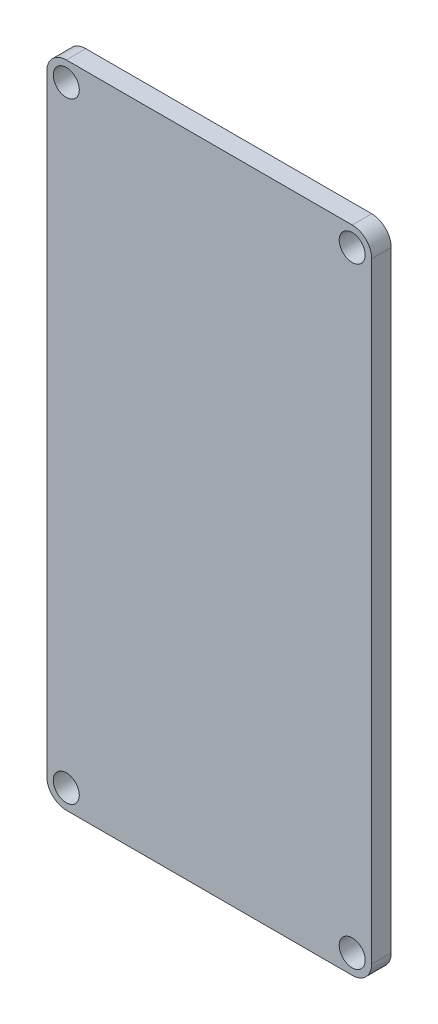
SolidWorks part; units mm, degrees
ref_plane "Front Plane" through (0, 0, 0) normal (0, 0, 1) x (1, 0, 0)
ref_plane "Top Plane" through (0, 0, 0) normal (0, 1, 0) x (1, 0, 0)
ref_plane "Right Plane" through (0, 0, 0) normal (1, 0, 0) x (0, 0, -1)
sketch "Sketch1" plane through (0, 0, 0) normal (0, 0, 1) x (1, 0, 0)
  line L1 (-22.007, -50.0002) -> (21.993, -50.0002)
  line L2 (-25.007, -47.0002) -> (-25.007, 46.9998)
  line L3 (-22.007, 49.9998) -> (21.993, 49.9998)
  line L4 (24.993, -47.0002) -> (24.993, 46.9998)
  line L5 (-25.007, -50.0002) -> (24.993, 49.9998) construction
  line L6 (-25.007, 49.9998) -> (24.993, -50.0002) construction
  line L7 (-22.007, -47.0002) -> (21.993, -47.0002)
  line L8 (-22.007, -47.0002) -> (-22.007, 46.9998)
  line L9 (-22.007, 46.9998) -> (21.993, 46.9998)
  line L10 (21.993, -47.0002) -> (21.993, 46.9998)
  line L11 (-22.007, -47.0002) -> (21.993, 46.9998) construction
  line L12 (-22.007, 46.9998) -> (21.993, -47.0002) construction
  arc A0 (-22.007, -50.0002) -> (-25.007, -47.0002) centre (-22.007, -47.0002) cw
  arc A1 (21.993, -50.0002) -> (24.993, -47.0002) centre (21.993, -47.0002) ccw
  arc A2 (21.993, 49.9998) -> (24.993, 46.9998) centre (21.993, 46.9998) cw
  arc A3 (-25.007, 46.9998) -> (-22.007, 49.9998) centre (-22.007, 46.9998) cw
  circle A4 centre (-22.007, 46.9998) radius 2
  circle A5 centre (21.993, 46.9998) radius 2
  circle A6 centre (21.993, -47.0002) radius 2
  circle A7 centre (-22.007, -47.0002) radius 2
  circle A8 centre (-22.007, 46.9998) radius 3
  circle A9 centre (21.993, 46.9998) radius 3
  circle A10 centre (21.993, -47.0002) radius 3
  circle A11 centre (-22.007, -47.0002) radius 3
  point P0 (-0.007, -0.0002)
  point P26 (-0.007, -0.0002)
  dimension "D3" = 3
  dimension "D4" = 4
  dimension "D1" = 100
  dimension "D2" = 50
extrude "Boss-Extrude1" add sketch "Sketch1" along normal blind 3 contours A9 L3 A8 L9 | L9 A8 A3 L8 A4 | A11 L7 A10 L10 A9 L9 A8 L8 | L8 A8 L9 A4 | A11 L8 A8 L2 | A2 A9 L9 A5 L10 | A10 L4 A9 L10 | L9 A9 L10 A5 | A1 A10 L10 A6 L7 | L10 A10 L7 A6 | A11 L1 A10 L7 | L8 A11 A0 L7 A7 | L7 A11 L8 A7
sketch "Sketch2" plane through (0, 0, 0) normal (0, 0, -1) x (-1, 0, 0)
  line L0 (12.5987, -31.1646) -> (12.5987, -29.7948)
  line L2 (12.5987, -29.7948) -> (20.007, -29.7948)
  line L3 (20.007, -29.7948) -> (20.007, -30.4596)
  line L4 (20.007, -30.4596) -> (13.3585, -30.4596)
  line L5 (13.3585, -30.4596) -> (13.3585, -31.5994)
  line L6 (13.3585, -31.5994) -> (12.5987, -31.1646)
  line L7 (14.8782, -11.6729) -> (14.8782, -12.3377)
  line L8 (17.2705, -9.1812) -> (19.2472, -11.0347)
  line L9 (19.2472, -11.0347) -> (19.2472, -7.5888)
  line L10 (19.2472, -7.5888) -> (20.007, -7.5888)
  line L11 (20.007, -7.5888) -> (20.007, -12.6227)
  line L12 (20.007, -12.6227) -> (16.941, -9.7496)
  line L13 (14.3083, 8.4436) -> (14.3083, 7.7787)
  line L14 (18.0125, 7.4938) -> (18.0125, 8.1587)
  line L15 (16.3029, 9.5833) -> (15.543, 9.5833)
  line L16 (12.4087, 31.6543) -> (12.4087, 31.7893)
  line L17 (12.4087, 31.7893) -> (17.5376, 31.7893)
  line L18 (17.5376, 31.7893) -> (17.5376, 32.6442)
  line L19 (17.5376, 32.6442) -> (18.2974, 32.6442)
  line L20 (18.2974, 32.6442) -> (18.2974, 31.7893)
  line L21 (18.2974, 31.7893) -> (20.007, 31.7893)
  line L22 (20.007, 31.7893) -> (20.007, 31.1245)
  line L23 (20.007, 31.1245) -> (18.2974, 31.1245)
  line L24 (18.2974, 31.1245) -> (18.2974, 27.6103)
  line L25 (18.2974, 27.6103) -> (12.4087, 31.6543)
  line L26 (17.5376, 31.1245) -> (14.3232, 31.1245)
  line L27 (14.3232, 31.1245) -> (17.5376, 28.9177)
  line L28 (17.5376, 28.9177) -> (17.5376, 31.1245)
  line L29 (0, -18.2359) -> (-7.4083, -18.2359)
  line L30 (-7.4083, -18.2359) -> (-7.4083, -16.74)
  line L31 (0, -15.9401) -> (0, -18.2359)
  line L32 (-0.7598, -17.571) -> (-0.7598, -16.7207)
  line L33 (-6.6485, -17.0501) -> (-6.6485, -17.571)
  line L34 (-6.6485, -17.571) -> (-0.7598, -17.571)
  line L35 (-7.4083, -10.6376) -> (-7.4083, -9.9728)
  line L36 (-7.4083, -9.9728) -> (0, -9.9728)
  line L37 (0, -9.9728) -> (0, -10.6376)
  line L38 (0, -10.6376) -> (-7.4083, -10.6376)
  line L39 (-6.1439, -1.4247) -> (-5.6037, -1.9946)
  line L40 (-2.8494, -1.6146) -> (-2.8494, -4.0841)
  line L41 (-2.8494, -4.0841) -> (-3.6092, -4.0841)
  line L42 (-3.6092, -4.0841) -> (-3.6092, -0.9498)
  line L43 (-7.4083, 0.5699) -> (-7.4083, 1.2347)
  line L44 (-7.4083, 1.2347) -> (0, 1.2347)
  line L45 (0, 1.2347) -> (0, 0.5699)
  line L46 (0, 0.5699) -> (-7.4083, 0.5699)
  line L47 (-6.6485, 1.9946) -> (-7.4083, 1.9946)
  line L48 (-7.4083, 1.9946) -> (-7.4083, 5.8887)
  line L49 (-7.4083, 5.8887) -> (-6.6485, 5.8887)
  line L50 (-6.6485, 5.8887) -> (-6.6485, 4.274)
  line L51 (-6.6485, 4.274) -> (0, 4.274)
  line L52 (0, 4.274) -> (0, 3.6092)
  line L53 (0, 3.6092) -> (-6.6485, 3.6092)
  line L54 (-6.6485, 3.6092) -> (-6.6485, 1.9946)
  line L55 (-7.4083, 10.2577) -> (0, 13.6769)
  line L56 (0, 13.6769) -> (0, 12.9542)
  line L57 (0, 12.9542) -> (-2.3745, 11.859)
  line L58 (-2.3745, 11.859) -> (-2.3745, 8.5006)
  line L59 (-2.3745, 8.5006) -> (0, 7.3757)
  line L60 (0, 7.3757) -> (0, 6.6485)
  line L61 (0, 6.6485) -> (-7.4083, 10.1627)
  line L62 (-7.4083, 10.1627) -> (-7.4083, 10.2577)
  line L63 (-5.9629, 10.2028) -> (-3.1343, 8.8627)
  line L64 (-3.1343, 8.8627) -> (-3.1343, 11.5087)
  line L65 (-3.1343, 11.5087) -> (-5.9629, 10.2028)
  line L66 (-7.4083, 14.8167) -> (-7.4083, 15.4815)
  line L67 (-7.4083, 15.4815) -> (-0.7598, 15.4815)
  line L68 (-0.7598, 15.4815) -> (-0.7598, 18.3309)
  line L69 (-0.7598, 18.3309) -> (0, 18.3309)
  line L70 (0, 18.3309) -> (0, 14.8167)
  line L71 (0, 14.8167) -> (-7.4083, 14.8167)
  spline S0 degree 3 poles (14.8782, -12.3377) (14.7048, -12.3335) (14.4502, -12.3057) (14.1228, -12.2279) (13.8944, -12.1474) (13.6772, -12.0472) (13.4719, -11.9272) (13.2793, -11.7849) (13.1012, -11.6236) (12.9378, -11.4484) (12.7967, -11.2594) (12.6775, -11.0608) (12.5778, -10.8531) (12.5031, -10.6341) (12.4277, -10.3253) (12.4084, -10.0842) (12.4087, -9.9217) knots 0 0 0 0 0.135103 0.198979 0.261904 0.323495 0.385195 0.446969 0.509765 0.572251 0.633405 0.693251 0.752583 0.812579 0.873275 1 1 1 1
  spline S1 degree 3 poles (12.4087, -9.9217) (12.4082, -9.7621) (12.4286, -9.5273) (12.4962, -9.2257) (12.5695, -9.0167) (12.6616, -8.8186) (12.7761, -8.6341) (12.9076, -8.4586) (13.0627, -8.3007) (13.2282, -8.1557) (13.4049, -8.0306) (13.5877, -7.923) (13.7779, -7.8349) (13.9762, -7.7681) (14.252, -7.7011) (14.4671, -7.6856) (14.6111, -7.6838) knots 0 0 0 0 0.136525 0.200801 0.263983 0.325711 0.387271 0.449493 0.512955 0.576266 0.637575 0.697901 0.757558 0.816588 0.876646 1 1 1 1
  spline S2 degree 3 poles (14.6111, -7.6838) (14.8157, -7.6829) (15.1211, -7.7226) (15.5107, -7.8502) (15.7452, -7.965) (15.9345, -8.079) (16.0901, -8.1824) (16.2569, -8.3044) (16.437, -8.4439) (16.6273, -8.6038) (16.9124, -8.8449) (17.1232, -9.045) (17.2705, -9.1812) knots 0 0 0 0 0.195649 0.292388 0.391297 0.444816 0.503919 0.570035 0.642593 0.721961 0.807944 1 1 1 1
  spline S3 degree 3 poles (16.941, -9.7496) (16.8011, -9.6149) (16.5982, -9.4228) (16.333, -9.1845) (16.1582, -9.0321) (15.996, -8.9012) (15.8516, -8.7851) (15.7188, -8.692) (15.5648, -8.591) (15.3768, -8.4933) (15.0715, -8.3809) (14.8301, -8.3485) (14.6704, -8.3486) knots 0 0 0 0 0.212829 0.306101 0.390647 0.466924 0.534481 0.593587 0.644557 0.7362 0.825024 1 1 1 1
  spline S4 degree 3 poles (14.6704, -8.3486) (14.5708, -8.3481) (14.4232, -8.3634) (14.2333, -8.4114) (14.0971, -8.4621) (13.9671, -8.529) (13.843, -8.6104) (13.723, -8.7044) (13.6105, -8.8131) (13.5074, -8.9325) (13.4161, -9.0586) (13.3398, -9.1921) (13.2773, -9.3323) (13.2283, -9.4788) (13.182, -9.6863) (13.169, -9.847) (13.1686, -9.9558) knots 0 0 0 0 0.122122 0.180988 0.239933 0.299906 0.359989 0.421776 0.486576 0.551535 0.615018 0.677259 0.73973 0.80305 0.866495 1 1 1 1
  spline S5 degree 3 poles (13.1686, -9.9558) (13.1687, -10.0697) (13.1826, -10.2375) (13.2273, -10.4545) (13.2793, -10.6057) (13.3409, -10.7512) (13.419, -10.8878) (13.5098, -11.018) (13.6151, -11.1395) (13.7335, -11.2505) (13.8639, -11.3493) (14.0054, -11.4351) (14.1575, -11.5101) (14.3217, -11.5709) (14.5613, -11.6347) (14.7493, -11.6637) (14.8782, -11.6729) knots 0 0 0 0 0.12653 0.186744 0.245898 0.304053 0.362196 0.420655 0.480331 0.540663 0.600744 0.661982 0.72448 0.789067 0.856333 1 1 1 1
  spline S6 degree 3 poles (14.3083, 7.7787) (14.1614, 7.8098) (13.9507, 7.8762) (13.6826, 7.9855) (13.5003, 8.0815) (13.3293, 8.1863) (13.1733, 8.3064) (13.0285, 8.4361) (12.9, 8.5797) (12.7837, 8.7303) (12.6844, 8.8899) (12.5991, 9.0555) (12.5288, 9.2281) (12.4759, 9.4083) (12.4237, 9.6594) (12.4078, 9.8533) (12.4087, 9.984) knots 0 0 0 0 0.141977 0.208985 0.273957 0.336889 0.398745 0.460116 0.520825 0.580994 0.640152 0.698622 0.757271 0.816427 0.876254 1 1 1 1
  spline S7 degree 3 poles (12.4087, 9.984) (12.4077, 10.1753) (12.4411, 10.4605) (12.5537, 10.824) (12.6689, 11.082) (12.8111, 11.3217) (12.9804, 11.5349) (13.1734, 11.7188) (13.3866, 11.8731) (13.6145, 11.9938) (13.9253, 12.1125) (14.1712, 12.1472) (14.3335, 12.1478) knots 0 0 0 0 0.17854 0.266093 0.354631 0.441886 0.525747 0.608114 0.690197 0.770821 0.848326 1 1 1 1
  spline S8 degree 3 poles (14.3335, 12.1478) (14.4865, 12.1475) (14.7143, 12.1243) (14.9998, 12.0306) (15.1988, 11.9353) (15.3844, 11.8118) (15.621, 11.6076) (15.7693, 11.4187) (15.8577, 11.2826) knots 0 0 0 0 0.250608 0.37063 0.490072 0.610375 0.734313 1 1 1 1
  spline S9 degree 3 poles (15.8577, 11.2826) (15.9265, 11.4421) (16.107, 11.7383) (16.3519, 11.9841) (16.4899, 12.0854) knots 0 0 0 0 0.503896 1 1 1 1
  spline S10 degree 3 poles (16.4899, 12.0854) (16.5843, 12.1596) (16.7369, 12.2522) (16.9485, 12.3582) (17.1118, 12.42) (17.2792, 12.4677) (17.5097, 12.5138) (17.687, 12.527) (17.8062, 12.5277) knots 0 0 0 0 0.254173 0.378112 0.501712 0.623986 0.747096 1 1 1 1
  spline S11 degree 3 poles (17.8062, 12.5277) (18.0134, 12.5293) (18.3248, 12.4838) (18.7216, 12.3434) (19.0077, 12.1946) (19.275, 12.0121) (19.516, 11.7975) (19.7199, 11.5476) (19.8923, 11.2714) (20.0288, 10.971) (20.1624, 10.5384) (20.1965, 10.1954) (20.197, 9.9647) knots 0 0 0 0 0.158908 0.239599 0.322582 0.406 0.487843 0.569676 0.65302 0.737412 0.822558 1 1 1 1
  spline S12 degree 3 poles (20.197, 9.9647) (20.1951, 9.8092) (20.1835, 9.5781) (20.121, 9.2822) (20.0633, 9.0727) (19.9834, 8.875) (19.8881, 8.6865) (19.7751, 8.5079) (19.644, 8.3402) (19.4974, 8.1837) (19.3326, 8.0423) (19.1529, 7.9145) (18.9565, 7.8011) (18.744, 7.7016) (18.431, 7.5873) (18.1836, 7.5239) (18.0125, 7.4938) knots 0 0 0 0 0.128956 0.190367 0.249965 0.308569 0.366415 0.424556 0.483181 0.542251 0.601744 0.662508 0.7245 0.789139 0.856354 1 1 1 1
  spline S13 degree 3 poles (18.0125, 8.1587) (18.1234, 8.1919) (18.2857, 8.2427) (18.4865, 8.3324) (18.6207, 8.4024) (18.7439, 8.4761) (18.8866, 8.5833) (18.9829, 8.6724) (19.0365, 8.7389) knots 0 0 0 0 0.291316 0.425966 0.55216 0.671527 0.786122 1 1 1 1
  spline S14 degree 3 poles (19.0365, 8.7389) (19.1023, 8.8201) (19.191, 8.951) (19.2838, 9.1406) (19.3407, 9.2916) (19.3833, 9.4513) (19.4254, 9.6794) (19.4382, 9.8565) (19.4372, 9.9766) knots 0 0 0 0 0.236156 0.35563 0.476249 0.600164 0.728633 1 1 1 1
  spline S15 degree 3 poles (19.4372, 9.9766) (19.4379, 10.1122) (19.4225, 10.3111) (19.3757, 10.5675) (19.323, 10.744) (19.2578, 10.9111) (19.176, 11.0664) (19.08, 11.212) (18.971, 11.346) (18.8515, 11.4666) (18.7266, 11.5727) (18.5968, 11.6629) (18.4612, 11.7357) (18.3205, 11.7931) (18.1246, 11.846) (17.9725, 11.8649) (17.87, 11.8628) knots 0 0 0 0 0.148752 0.218403 0.28576 0.350598 0.414964 0.478069 0.541761 0.60435 0.664075 0.721464 0.777587 0.832644 0.887844 1 1 1 1
  spline S16 degree 3 poles (17.87, 11.8628) (17.7325, 11.8621) (17.5245, 11.8311) (17.2653, 11.7221) (17.0798, 11.61) (16.91, 11.4701) (16.7574, 11.3092) (16.6316, 11.1228) (16.5446, 10.9513) (16.4853, 10.7994) (16.4457, 10.6694) (16.4123, 10.5239) (16.3811, 10.3645) (16.3546, 10.1902) (16.324, 9.9288) (16.31, 9.7245) (16.3029, 9.5833) knots 0 0 0 0 0.13348 0.201027 0.271634 0.342905 0.413859 0.485996 0.560246 0.599899 0.644068 0.691904 0.744697 0.801499 0.862863 1 1 1 1
  spline S17 degree 3 poles (15.543, 9.5833) (15.5437, 9.7627) (15.5238, 10.0275) (15.4499, 10.3673) (15.3727, 10.6013) (15.2817, 10.8142) (15.1765, 10.9997) (15.0575, 11.1528) (14.9269, 11.2752) (14.7876, 11.3681) (14.5934, 11.4575) (14.4351, 11.4822) (14.3306, 11.4829) knots 0 0 0 0 0.215729 0.318104 0.417658 0.511742 0.59626 0.673405 0.744145 0.810662 0.874049 1 1 1 1
  spline S18 degree 3 poles (14.3306, 11.4829) (14.2535, 11.4848) (14.1392, 11.4692) (13.9927, 11.4258) (13.888, 11.3793) (13.7879, 11.3189) (13.6911, 11.2461) (13.5989, 11.1588) (13.5109, 11.061) (13.4309, 10.9527) (13.3608, 10.8364) (13.3014, 10.7127) (13.2522, 10.5822) (13.2153, 10.4444) (13.1791, 10.2483) (13.1691, 10.0961) (13.1686, 9.9929) knots 0 0 0 0 0.109958 0.163912 0.218089 0.273309 0.330914 0.390994 0.454641 0.518898 0.583342 0.648543 0.715053 0.782519 0.852334 1 1 1 1
  spline S19 degree 3 poles (13.1686, 9.9929) (13.1682, 9.8284) (13.1982, 9.5858) (13.3081, 9.2855) (13.404, 9.1167) (13.4987, 8.9921) (13.5814, 8.903) (13.6734, 8.8156) (13.7802, 8.7354) (13.8946, 8.6545) (14.0701, 8.5531) (14.2101, 8.4854) (14.3083, 8.4436) knots 0 0 0 0 0.239685 0.351816 0.463766 0.520818 0.579448 0.640604 0.705298 0.773634 0.844669 1 1 1 1
  spline S20 degree 3 poles (-7.4083, -16.74) (-7.4073, -16.4886) (-7.402, -16.1252) (-7.3738, -15.6592) (-7.3443, -15.3513) (-7.3079, -15.0709) (-7.2505, -14.7507) (-7.1899, -14.5269) (-7.1412, -14.3893) knots 0 0 0 0 0.317406 0.458844 0.589367 0.707831 0.81577 1 1 1 1
  spline S21 degree 3 poles (-7.1412, -14.3893) (-7.0807, -14.2183) (-6.9698, -13.9713) (-6.7843, -13.665) (-6.6279, -13.4523) (-6.4547, -13.2543) (-6.2659, -13.0687) (-6.0573, -12.9001) (-5.8328, -12.7458) (-5.5951, -12.6066) (-5.3446, -12.4857) (-5.0826, -12.3853) (-4.8099, -12.3019) (-4.5259, -12.2362) (-4.1259, -12.1752) (-3.8185, -12.1562) (-3.6107, -12.1573) knots 0 0 0 0 0.121697 0.181159 0.240077 0.298686 0.357633 0.417592 0.478482 0.540397 0.602336 0.664997 0.728553 0.793646 0.860531 1 1 1 1
  spline S22 degree 3 poles (-3.6107, -12.1573) (-3.4302, -12.1565) (-3.1635, -12.1724) (-2.8147, -12.2191) (-2.5657, -12.272) (-2.3237, -12.3364) (-2.0913, -12.4189) (-1.8662, -12.5133) (-1.6515, -12.6235) (-1.4482, -12.7446) (-1.2564, -12.8737) (-1.0804, -13.0138) (-0.9156, -13.1607) (-0.7663, -13.318) (-0.6298, -13.4838) (-0.5085, -13.6586) (-0.4004, -13.8437) (-0.3037, -14.0414) (-0.223, -14.258) (-0.1531, -14.4924) (-0.0976, -14.746) (-0.0528, -15.0179) (-0.0115, -15.4177) (0.0011, -15.7276) (0, -15.9401) knots 0 0 0 0 0.090813 0.134304 0.177036 0.218837 0.260262 0.3011 0.341637 0.381609 0.420148 0.45791 0.494761 0.531219 0.566961 0.602742 0.638232 0.674761 0.713378 0.754425 0.797802 0.843979 0.893064 1 1 1 1
  spline S23 degree 3 poles (-0.7598, -16.7207) (-0.7599, -16.4857) (-0.7644, -16.1476) (-0.7847, -15.7168) (-0.805, -15.4371) (-0.8319, -15.1867) (-0.8689, -14.9096) (-0.9119, -14.7185) (-0.9483, -14.603) knots 0 0 0 0 0.330628 0.475549 0.606746 0.725024 0.829742 1 1 1 1
  spline S24 degree 3 poles (-0.9483, -14.603) (-0.9937, -14.469) (-1.0695, -14.2717) (-1.2067, -14.0299) (-1.3197, -13.8604) (-1.4481, -13.703) (-1.589, -13.5561) (-1.7432, -13.4198) (-1.9102, -13.2961) (-2.0884, -13.1841) (-2.2781, -13.0879) (-2.4766, -13.0042) (-2.6854, -12.9379) (-2.9031, -12.8856) (-3.212, -12.8357) (-3.4505, -12.8222) (-3.6122, -12.8221) knots 0 0 0 0 0.123333 0.183117 0.241773 0.300566 0.359665 0.418864 0.479511 0.540462 0.601913 0.664467 0.727807 0.792475 0.859249 1 1 1 1
  spline S25 degree 3 poles (-3.6122, -12.8221) (-3.7824, -12.8202) (-4.0332, -12.8379) (-4.359, -12.8914) (-4.5896, -12.948) (-4.8112, -13.0203) (-5.0225, -13.1105) (-5.2257, -13.2135) (-5.4162, -13.336) (-5.5963, -13.4703) (-5.7613, -13.6192) (-5.9115, -13.7806) (-6.0494, -13.9525) (-6.1693, -14.1399) (-6.3145, -14.4079) (-6.3946, -14.6253) (-6.4407, -14.7736) knots 0 0 0 0 0.137813 0.203226 0.267174 0.330024 0.391794 0.453084 0.514334 0.575 0.634865 0.694116 0.753442 0.813126 0.87408 1 1 1 1
  spline S26 degree 3 poles (-6.4407, -14.7736) (-6.4804, -14.9049) (-6.5254, -15.1196) (-6.5694, -15.426) (-6.5992, -15.6967) (-6.6205, -15.9953) (-6.643, -16.4493) (-6.6493, -16.8042) (-6.6485, -17.0501) knots 0 0 0 0 0.179285 0.286583 0.405111 0.535593 0.67819 1 1 1 1
  spline S27 degree 3 poles (-5.6037, -1.9946) (-5.8006, -2.1933) (-6.0666, -2.5134) (-6.3558, -2.98) (-6.5295, -3.3392) (-6.6654, -3.7028) (-6.7962, -4.1771) (-6.8392, -4.5381) (-6.8385, -4.7756) knots 0 0 0 0 0.269021 0.398733 0.527306 0.652311 0.771699 1 1 1 1
  spline S28 degree 3 poles (-6.8385, -4.7756) (-6.8403, -4.9191) (-6.8246, -5.1328) (-6.7814, -5.4145) (-6.735, -5.6227) (-6.6761, -5.8286) (-6.6025, -6.0315) (-6.5166, -6.2319) (-6.4175, -6.4278) (-6.3085, -6.6178) (-6.1877, -6.7972) (-6.0591, -6.9672) (-5.9192, -7.1245) (-5.7696, -7.2703) (-5.6129, -7.4072) (-5.446, -7.5327) (-5.2697, -7.6444) (-5.0879, -7.7453) (-4.9023, -7.8325) (-4.7145, -7.9083) (-4.5233, -7.966) (-4.3305, -8.0149) (-4.0691, -8.0606) (-3.8697, -8.0715) (-3.7368, -8.0732) knots 0 0 0 0 0.085568 0.127714 0.170062 0.212779 0.255472 0.298866 0.342848 0.386513 0.429516 0.471868 0.51371 0.555061 0.596513 0.637859 0.67956 0.721068 0.76189 0.801925 0.841812 0.881065 0.920636 1 1 1 1
  spline S29 degree 3 poles (-3.7368, -8.0732) (-3.6005, -8.0716) (-3.3957, -8.0608) (-3.1279, -8.0099) (-2.9301, -7.9596) (-2.7346, -7.8955) (-2.5416, -7.8167) (-2.3512, -7.723) (-2.1653, -7.6147) (-1.9843, -7.495) (-1.8124, -7.3635) (-1.6516, -7.2198) (-1.4995, -7.0665) (-1.3571, -6.9024) (-1.2261, -6.7257) (-1.1044, -6.5389) (-0.9935, -6.3421) (-0.8944, -6.1372) (-0.8063, -5.9271) (-0.7338, -5.7111) (-0.6746, -5.4904) (-0.6262, -5.2653) (-0.584, -4.9555) (-0.5677, -4.7202) (-0.5699, -4.5619) knots 0 0 0 0 0.077886 0.116658 0.155425 0.194361 0.234007 0.274295 0.315417 0.356772 0.398061 0.438867 0.479803 0.521246 0.562815 0.605269 0.648388 0.691709 0.735134 0.778356 0.821651 0.865516 0.909726 1 1 1 1
  spline S30 degree 3 poles (-0.5699, -4.5619) (-0.5701, -4.3733) (-0.5892, -4.0946) (-0.6545, -3.7337) (-0.7248, -3.4792) (-0.8138, -3.2356) (-0.924, -3.0038) (-1.054, -2.7832) (-1.2013, -2.5746) (-1.3655, -2.3831) (-1.541, -2.2088) (-1.7302, -2.0577) (-1.9303, -1.9253) (-2.1432, -1.816) (-2.4453, -1.6946) (-2.6858, -1.6392) (-2.8494, -1.6146) knots 0 0 0 0 0.138708 0.204939 0.269469 0.332671 0.395498 0.457967 0.520867 0.583068 0.643278 0.702549 0.760882 0.819471 0.878256 1 1 1 1
  spline S31 degree 3 poles (-3.6092, -0.9498) (-3.3322, -0.9516) (-2.9249, -0.9805) (-2.4044, -1.0902) (-2.0446, -1.1994) (-1.7074, -1.341) (-1.3924, -1.5132) (-1.1016, -1.7189) (-0.8327, -1.9507) (-0.5928, -2.2108) (-0.382, -2.4923) (-0.2044, -2.7955) (-0.0599, -3.1202) (0.0528, -3.4654) (0.1622, -3.9645) (0.1889, -4.3548) (0.19, -4.6198) knots 0 0 0 0 0.139493 0.204635 0.267406 0.328446 0.388397 0.447734 0.507392 0.566768 0.625478 0.684067 0.743248 0.804033 0.866499 1 1 1 1
  spline S32 degree 3 poles (0.19, -4.6198) (0.1896, -4.7848) (0.1788, -5.0288) (0.1435, -5.3489) (0.1043, -5.579) (0.0562, -5.8033) (-0.0054, -6.0205) (-0.0767, -6.2315) (-0.1577, -6.4366) (-0.2516, -6.6341) (-0.356, -6.8246) (-0.4703, -7.0094) (-0.5965, -7.1871) (-0.7336, -7.3586) (-0.9326, -7.5793) (-1.0968, -7.7323) (-1.211, -7.8298) knots 0 0 0 0 0.136557 0.202094 0.266464 0.329769 0.391879 0.453271 0.514115 0.57439 0.634142 0.693923 0.754152 0.81447 0.875661 1 1 1 1
  spline S33 degree 3 poles (-1.211, -7.8298) (-1.3868, -7.9771) (-1.6648, -8.1765) (-2.0647, -8.3878) (-2.3728, -8.5157) (-2.6917, -8.6154) (-3.1347, -8.7121) (-3.4773, -8.7362) (-3.7071, -8.738) knots 0 0 0 0 0.253668 0.376738 0.499344 0.621999 0.745699 1 1 1 1
  spline S34 degree 3 poles (-3.7071, -8.738) (-3.8804, -8.7401) (-4.1384, -8.7212) (-4.477, -8.6685) (-4.7248, -8.6113) (-4.9679, -8.5391) (-5.2066, -8.4491) (-5.4409, -8.3442) (-5.6692, -8.2223) (-5.8886, -8.0867) (-6.0979, -7.9394) (-6.2938, -7.7792) (-6.4768, -7.6056) (-6.6495, -7.4223) (-6.8083, -7.2253) (-6.9558, -7.0175) (-7.0891, -6.7975) (-7.2088, -6.5686) (-7.3138, -6.3314) (-7.4005, -6.086) (-7.4741, -5.8341) (-7.5285, -5.574) (-7.5821, -5.2143) (-7.6003, -4.9389) (-7.5983, -4.7534) knots 0 0 0 0 0.083545 0.124644 0.165305 0.206173 0.246974 0.288333 0.32999 0.371802 0.412742 0.453464 0.493833 0.534375 0.574947 0.615887 0.657246 0.699003 0.740483 0.782323 0.824565 0.86704 0.910499 1 1 1 1
  spline S35 degree 3 poles (-7.5983, -4.7534) (-7.5978, -4.6013) (-7.5871, -4.3744) (-7.551, -4.0754) (-7.5146, -3.8558) (-7.4649, -3.64) (-7.4055, -3.4276) (-7.3363, -3.2181) (-7.2538, -3.0123) (-7.1601, -2.8088) (-7.0547, -2.6064) (-6.9356, -2.4058) (-6.8027, -2.2067) (-6.6581, -2.0079) (-6.4414, -1.7432) (-6.268, -1.5494) (-6.1439, -1.4247) knots 0 0 0 0 0.122179 0.182216 0.241864 0.30096 0.359969 0.419033 0.478069 0.537993 0.59896 0.661321 0.725248 0.79122 0.858746 1 1 1 1
  point P6 (20.007, 0)
  point P288 (0, 0)
  point P289 (0, 0)
  point P290 (0, 0)
  point P291 (0, 0)
extrude "Boss-Extrude2" add sketch "Sketch2" along normal blind 1
